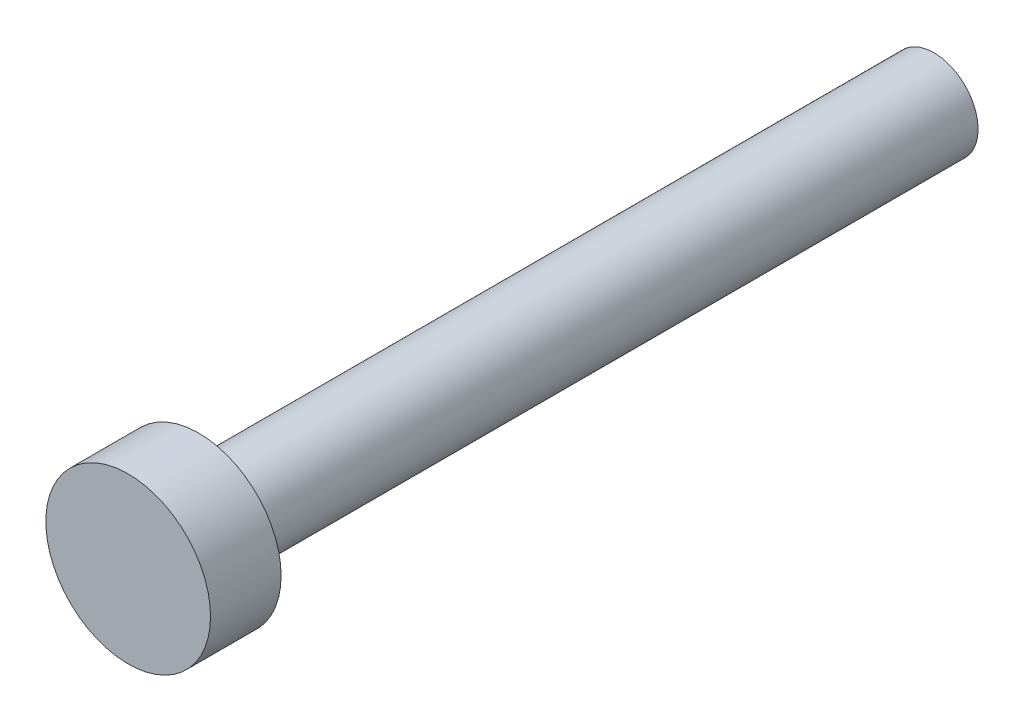
SolidWorks part; units mm, degrees
ref_plane "Plan de face" through (0, 0, 0) normal (0, 0, 1) x (1, 0, 0)
ref_plane "Plan de dessus" through (0, 0, 0) normal (0, 1, 0) x (1, 0, 0)
ref_plane "Plan de droite" through (0, 0, 0) normal (1, 0, 0) x (0, 0, -1)
sketch "Esquisse1" plane through (0, 0, 0) normal (0, 0, 1) x (1, 0, 0)
  circle A0 centre (0, 0) radius 2.8
  dimension "D1" = 5.6
extrude "Boss.-Extru.1" add sketch "Esquisse1" along normal blind 2.4
sketch "Esquisse2" plane through (0, 0, 0) normal (0, 0, -1) x (-1, 0, 0)
  circle A0 centre (0, 0) radius 1.5
  dimension "D1" = 3
extrude "Boss.-Extru.2" add sketch "Esquisse2" along normal blind 25
